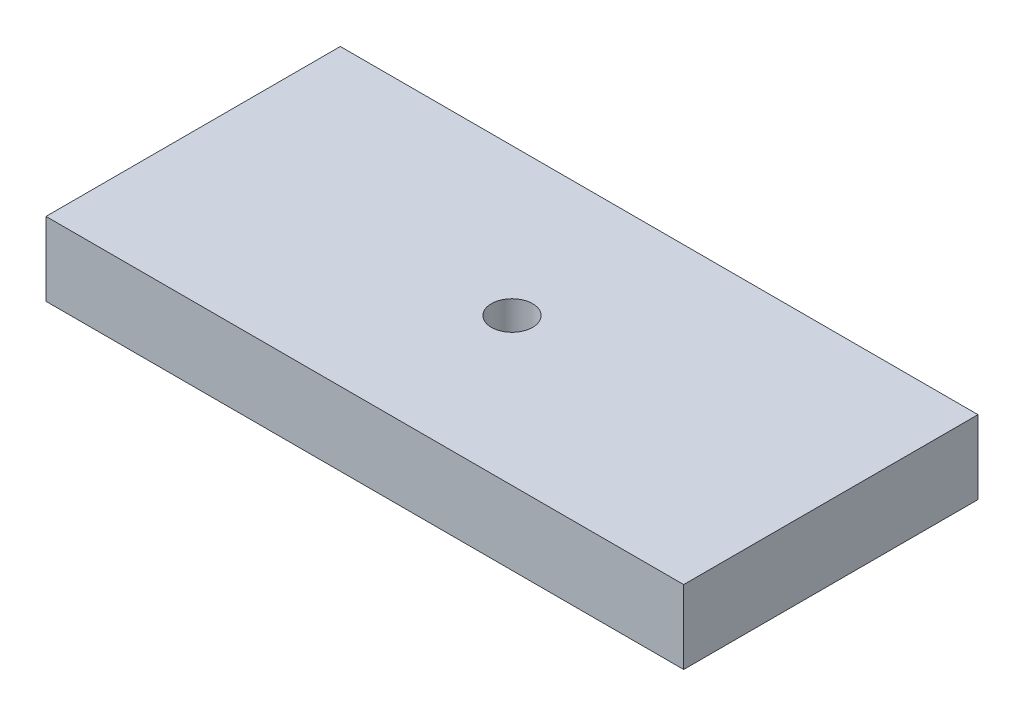
SolidWorks part; units mm, degrees
ref_plane "Front Plane" through (0, 0, 0) normal (0, 0, 1) x (1, 0, 0)
ref_plane "Top Plane" through (0, 0, 0) normal (0, 1, 0) x (1, 0, 0)
ref_plane "Right Plane" through (0, 0, 0) normal (1, 0, 0) x (0, 0, -1)
sketch "Sketch1" plane through (0, 0, 0) normal (0, 1, 0) x (1, 0, 0)
  line L1 (-65, -30) -> (65, -30)
  line L2 (-65, -30) -> (-65, 30)
  line L3 (-65, 30) -> (65, 30)
  line L4 (65, -30) -> (65, 30)
  line L5 (-65, -30) -> (65, 30) construction
  line L6 (-65, 30) -> (65, -30) construction
  point P0 (0, 0)
  dimension "D1" = 130
  dimension "D2" = 60
extrude "Boss-Extrude1" add sketch "Sketch1" along normal blind 15
sketch "Sketch2" plane through (0, 15, 0) normal (0, 1, 0) x (1, 0, 0)
  circle A0 centre (0, 0) radius 4.1956
extrude "Cut-Extrude1" cut sketch "Sketch2" against normal through all
